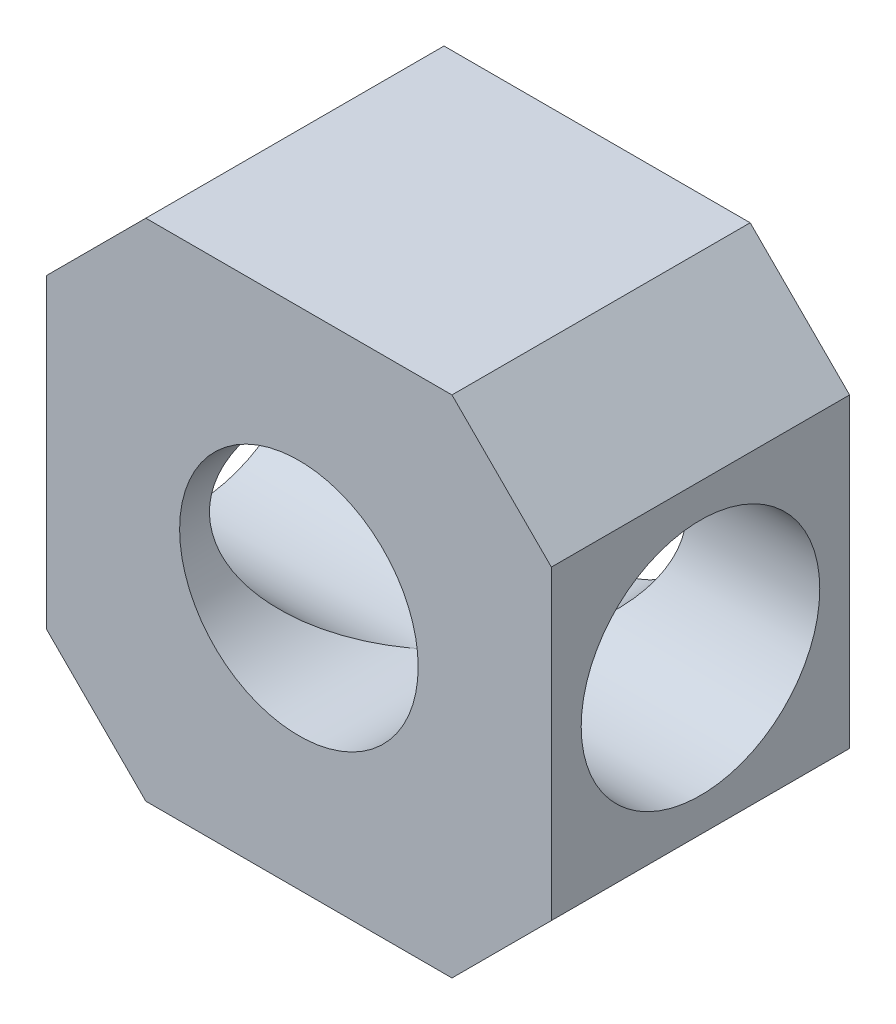
SolidWorks part; units mm, degrees
ref_plane "Front Plane" through (0, 0, 0) normal (0, 0, 1) x (1, 0, 0)
ref_plane "Top Plane" through (0, 0, 0) normal (0, 1, 0) x (1, 0, 0)
ref_plane "Right Plane" through (0, 0, 0) normal (1, 0, 0) x (0, 0, -1)
sketch "Sketch1" plane through (0, 0, 0) normal (0, 0, 1) x (1, 0, 0)
  line L1 (0, 0) -> (-25.4, 0)
  line L2 (0, 0) -> (0, 25.4)
  line L3 (0, 25.4) -> (-25.4, 25.4)
  line L4 (-25.4, 0) -> (-25.4, 25.4)
  dimension "D1" = 25.4
extrude "Boss-Extrude1" add sketch "Sketch1" along normal blind 15 contours L2 L1 L4 L3
chamfer "Chamfer1" distance 5 angle 45 4 edges at (0, 0, 7.5) (-25.4, 0, 7.5) (-25.4, 25.4, 7.5) (0, 25.4, 7.5)
sketch "Sketch2" plane through (0, 0, 15) normal (0, 0, 1) x (1, 0, 0)
  line L0 (-12.7, 25.4) -> (-12.7, 0) construction
  line L1 (-12.7, 0) -> (0, 12.7) construction
  line L2 (0, 12.7) -> (-25.4, 12.7) construction
  line L8 (-20.4, 0) -> (-5, 0)
  line L9 (-5, 0) -> (0, 5)
  line L10 (0, 5) -> (0, 20.4)
  line L11 (0, 20.4) -> (-5, 25.4)
  line L12 (-5, 25.4) -> (-20.4, 25.4)
  line L13 (-20.4, 25.4) -> (-25.4, 20.4)
  line L14 (-25.4, 20.4) -> (-25.4, 5)
  line L15 (-25.4, 5) -> (-20.4, 0)
  line L16 (-20.4, 0) -> (-5, 0)
  line L17 (-5, 0) -> (0, 5)
  line L18 (0, 5) -> (0, 20.4)
  line L19 (0, 20.4) -> (-5, 25.4)
  line L20 (-5, 25.4) -> (-20.4, 25.4)
  line L21 (-20.4, 25.4) -> (-25.4, 20.4)
  line L22 (-25.4, 20.4) -> (-25.4, 5)
  line L23 (-25.4, 5) -> (-20.4, 0)
  circle A0 centre (-12.7, 12.7) radius 6
  point P10 (-12.7, 12.7)
  dimension "D2" = 12
  dimension "D1" = 0
extrude "Cut-Extrude1" cut sketch "Sketch2" against normal through all contours A0
sketch "Sketch3" plane through (0, 0, 0) normal (1, 0, 0) x (0, 0, -1)
  line L0 (-15, 25.4) -> (-15, 20.4) construction
  line L1 (-15, 20.4) -> (0, 20.4) construction
  line L2 (0, 20.4) -> (0, 25.4) construction
  line L3 (0, 25.4) -> (-15, 25.4) construction
  line L4 (-15, 20.4) -> (-15, 5)
  line L5 (-15, 5) -> (0, 5)
  line L6 (0, 5) -> (0, 20.4)
  line L7 (0, 20.4) -> (-15, 20.4)
  line L8 (-15, 20.4) -> (-15, 5)
  line L9 (-15, 5) -> (0, 5)
  line L10 (0, 5) -> (0, 20.4)
  line L11 (0, 20.4) -> (-15, 20.4)
  line L12 (-15, 5) -> (-15, 0) construction
  line L13 (-15, 0) -> (0, 0) construction
  line L14 (0, 0) -> (0, 5) construction
  line L15 (0, 5) -> (-15, 5) construction
  line L16 (-15, 25.4) -> (-15, 20.4)
  line L17 (-15, 20.4) -> (0, 20.4)
  line L18 (0, 20.4) -> (0, 25.4)
  line L19 (0, 25.4) -> (-15, 25.4)
  line L20 (-15, 5) -> (-15, 0)
  line L21 (-15, 0) -> (0, 0)
  line L22 (0, 0) -> (0, 5)
  line L23 (0, 5) -> (-15, 5)
  line L24 (-7.5, 25.4) -> (-7.5, 0) construction
  line L26 (-15, 12.7) -> (0, 12.7) construction
  circle A0 centre (-7.5, 12.7) radius 6
  point P15 (-7.5, 12.7)
  dimension "D2" = 12
  dimension "D1" = 0
extrude "Cut-Extrude2" cut sketch "Sketch3" against normal through all contours A0
